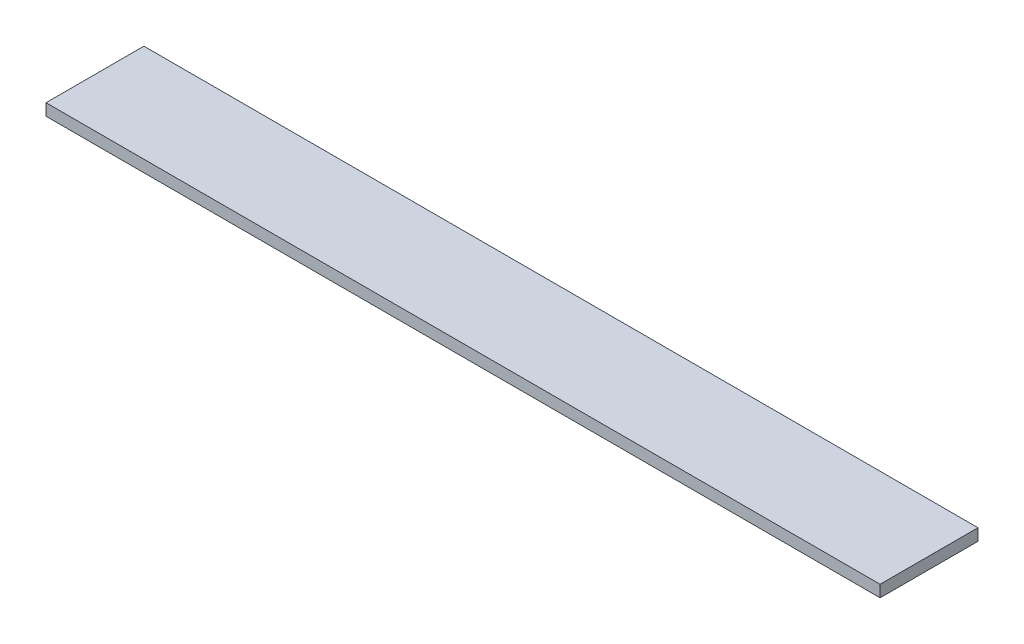
SolidWorks part; units mm, degrees
material "Silicon Rubber"
ref_plane "Front Plane" through (0, 0, 0) normal (0, 0, 1) x (1, 0, 0)
ref_plane "Top Plane" through (0, 0, 0) normal (0, 1, 0) x (1, 0, 0)
ref_plane "Right Plane" through (0, 0, 0) normal (1, 0, 0) x (0, 0, -1)
sketch "Sketch1" plane through (0, 0, 0) normal (0, 1, 0) x (1, 0, 0)
  line L1 (-135.255, 15.875) -> (135.255, 15.875)
  line L2 (-135.255, 15.875) -> (-135.255, -15.875)
  line L3 (-135.255, -15.875) -> (135.255, -15.875)
  line L4 (135.255, 15.875) -> (135.255, -15.875)
  line L5 (-135.255, 15.875) -> (135.255, -15.875) construction
  line L6 (-135.255, -15.875) -> (135.255, 15.875) construction
  point P0 (0, 0)
  dimension "D1" = 270.51
  dimension "D2" = 31.75
extrude "Boss-Extrude1" add sketch "Sketch1" along normal blind 3.81
